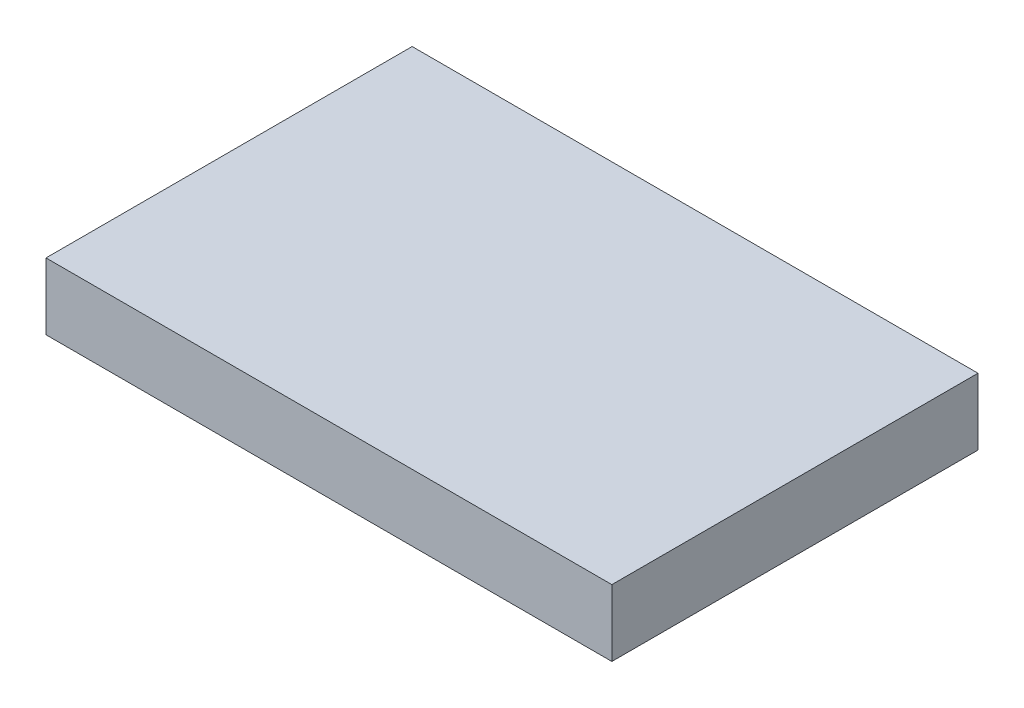
SolidWorks part; units mm, degrees
ref_plane "Front Plane" through (0, 0, 0) normal (0, 0, 1) x (1, 0, 0)
ref_plane "Top Plane" through (0, 0, 0) normal (0, 1, 0) x (1, 0, 0)
ref_plane "Right Plane" through (0, 0, 0) normal (1, 0, 0) x (0, 0, -1)
sketch "Sketch1" plane through (0, 0, 0) normal (0, 1, 0) x (1, 0, 0)
  line L1 (-42.5, -27.5) -> (42.5, -27.5)
  line L2 (-42.5, -27.5) -> (-42.5, 27.5)
  line L3 (-42.5, 27.5) -> (42.5, 27.5)
  line L4 (42.5, -27.5) -> (42.5, 27.5)
  line L5 (-42.5, -27.5) -> (42.5, 27.5) construction
  line L6 (-42.5, 27.5) -> (42.5, -27.5) construction
  point P0 (0, 0)
  dimension "D1" = 85
  dimension "D2" = 55
extrude "Boss-Extrude1" add sketch "Sketch1" along normal blind 10
